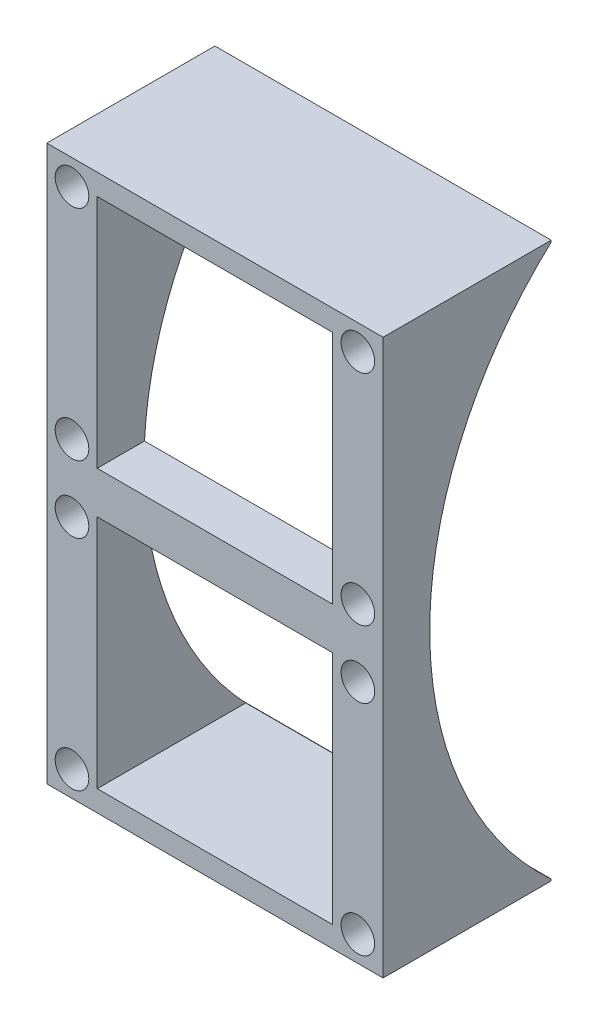
SolidWorks part; units mm, degrees
ref_plane "Front Plane" through (0, 0, 0) normal (0, 0, 1) x (1, 0, 0)
ref_plane "Top Plane" through (0, 0, 0) normal (0, 1, 0) x (1, 0, 0)
ref_plane "Right Plane" through (0, 0, 0) normal (1, 0, 0) x (0, 0, -1)
sketch "Sketch1" plane through (0, 0, 0) normal (0, 0, 1) x (1, 0, 0)
  line L0 (0, -33) -> (0, -16.5) construction
  line L1 (-20, 33) -> (20, 33)
  line L2 (-20, 33) -> (-20, -33)
  line L3 (-20, -33) -> (20, -33)
  line L4 (20, 33) -> (20, -33)
  line L5 (-20, 33) -> (20, -33) construction
  line L6 (-20, -33) -> (20, 33) construction
  line L7 (0, 33) -> (0, 16.5) construction
  line L9 (-14, 30.5) -> (14, 30.5)
  line L10 (-14, 30.5) -> (-14, 2.5)
  line L11 (-14, 2.5) -> (14, 2.5)
  line L12 (14, 30.5) -> (14, 2.5)
  line L13 (-14, 30.5) -> (14, 2.5) construction
  line L14 (-14, 2.5) -> (14, 30.5) construction
  line L15 (-14, -2.5) -> (14, -2.5)
  line L16 (-14, -2.5) -> (-14, -30.5)
  line L17 (-14, -30.5) -> (14, -30.5)
  line L18 (14, -2.5) -> (14, -30.5)
  line L19 (-14, -2.5) -> (14, -30.5) construction
  line L20 (-14, -30.5) -> (14, -2.5) construction
  point P0 (0, 0)
  dimension "D1" = 40
  dimension "D2" = 66
  dimension "D3" = 28
  dimension "D4" = 28
  dimension "D5" = 28
  dimension "D6" = 28
extrude "Boss-Extrude1" add sketch "Sketch1" along normal blind 20
sketch "Sketch3" plane through (0, 0, 0) normal (1, 0, 0) x (0, 0, -1)
  line L0 (0, 0) -> (30, 0) construction
  circle A0 centre (30, 0) radius 44.45
  point P4 (0, 0)
  point P5 (0, 0)
  dimension "D1" = 88.9
  dimension "D2" = 30
extrude "Cut-Extrude1" cut sketch "Sketch3" against normal blind 27 and the other way blind 26
sketch "Sketch4" plane through (0, 0, 20) normal (0, 0, 1) x (1, 0, 0)
  circle A0 centre (-17, 30) radius 2
  circle A1 centre (17, 30) radius 2
  circle A2 centre (-17, -30) radius 2
  circle A3 centre (17, -30) radius 2
  dimension "D1" = 4
  dimension "D4" = 4
  dimension "D7" = 4
  dimension "D10" = 4
  dimension "D2" = 3
  dimension "D3" = 3
  dimension "D5" = 3
  dimension "D6" = 3
  dimension "D8" = 3
  dimension "D9" = 3
  dimension "D11" = 3
  dimension "D12" = 3
extrude "Cut-Extrude2" cut sketch "Sketch4" against normal blind 27
sketch "Sketch5" plane through (0, 0, 20) normal (0, 0, 1) x (1, 0, 0)
  line L0 (0, 0) -> (-20, 0) construction
  line L1 (-20, 33) -> (-20, -33) construction
  line L2 (0, 0) -> (20, 0) construction
  line L3 (20, -33) -> (20, 33) construction
  line L4 (-17, 0) -> (-17, 4) construction
  line L5 (-17, 0) -> (-17, -4) construction
  line L6 (17, 0) -> (17, 4) construction
  line L7 (17, 0) -> (17, -4) construction
  circle A1 centre (-17, 4) radius 2
  circle A2 centre (-17, -4) radius 2
  circle A3 centre (17, 4) radius 2
  circle A4 centre (17, -4) radius 2
  point P5 (-17, 0)
  point P9 (17, 0)
  dimension "D3" = 4
  dimension "D4" = 4
  dimension "D5" = 4
  dimension "D6" = 4
  dimension "D1" = 3
  dimension "D2" = 3
extrude "Cut-Extrude3" cut sketch "Sketch5" against normal through all
